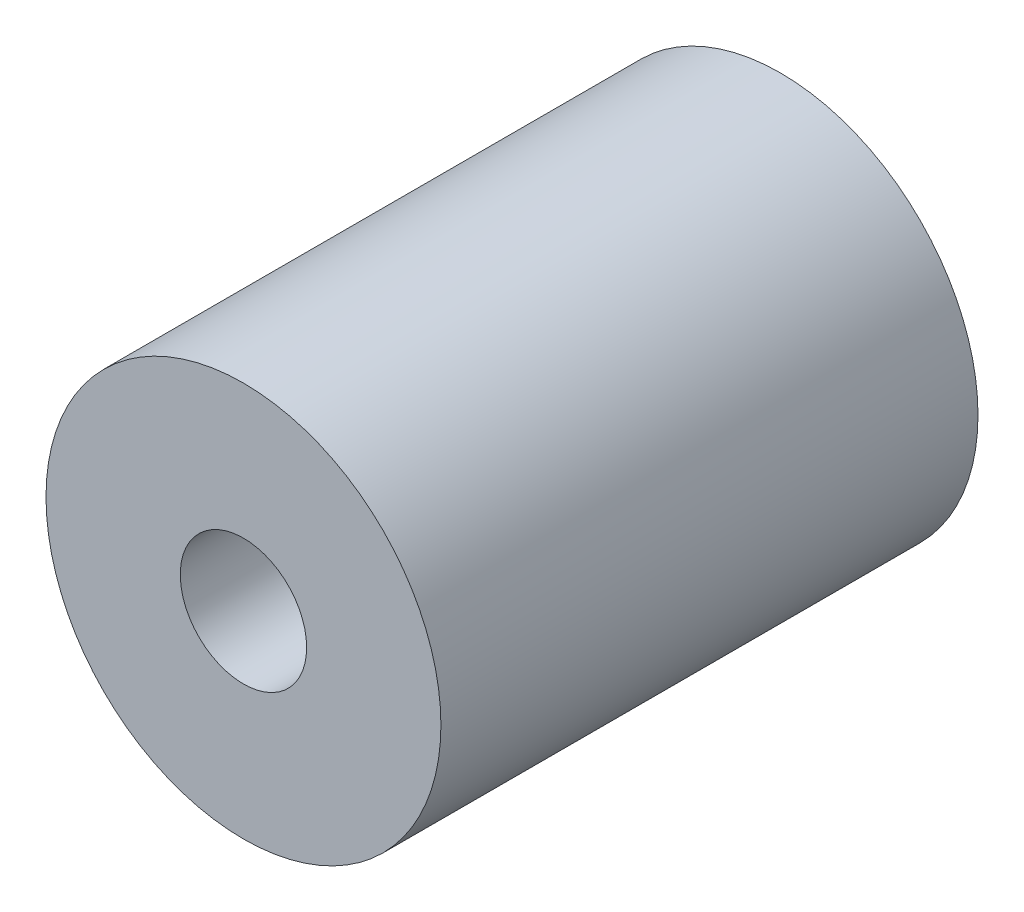
SolidWorks part; units mm, degrees
material "3.3535 (EN-AW 5754)"
ref_plane "Ebene vorne" through (0, 0, 0) normal (0, 0, 1) x (1, 0, 0)
ref_plane "Ebene oben" through (0, 0, 0) normal (0, 1, 0) x (1, 0, 0)
ref_plane "Ebene rechts" through (0, 0, 0) normal (1, 0, 0) x (0, 0, -1)
sketch "Skizze1" plane through (0, 0, 0) normal (0, 0, 1) x (1, 0, 0)
  circle A0 centre (0, 0) radius 12.5
  dimension "D1" = 25
extrude "Aufsatz-Linear austragen1" add sketch "Skizze1" along normal blind 34
sketch "Skizze2" plane through (0, 0, 34) normal (0, 0, 1) x (1, 0, 0)
  circle A0 centre (0, 0) radius 4
  dimension "D1" = 8
extrude "Schnitt-Linear austragen1" cut sketch "Skizze2" against normal blind 12
sketch "Skizze3" plane through (0, 0, 0) normal (0, 0, -1) x (-1, 0, 0)
  circle A0 centre (0, 0) radius 6
  dimension "D1" = 12
extrude "Schnitt-Linear austragen2" cut sketch "Skizze3" against normal blind 12
